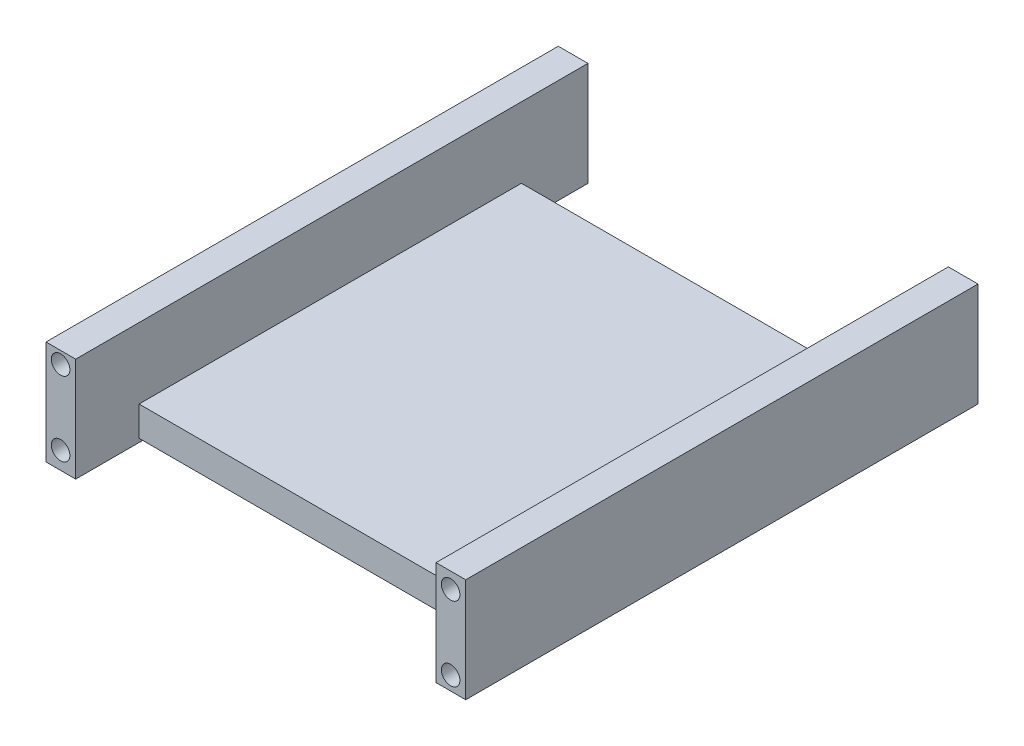
SolidWorks part; units mm, degrees
ref_plane "前视基准面" through (0, 0, 0) normal (0, 0, 1) x (1, 0, 0)
ref_plane "上视基准面" through (0, 0, 0) normal (0, 1, 0) x (1, 0, 0)
ref_plane "右视基准面" through (0, 0, 0) normal (1, 0, 0) x (0, 0, -1)
sketch "草图1" plane through (0, 0, 0) normal (1, 0, 0) x (0, 0, -1)
  line L1 (-69, 14) -> (69, 14)
  line L2 (-69, 14) -> (-69, -14)
  line L3 (-69, -14) -> (69, -14)
  line L4 (69, 14) -> (69, -14)
  line L5 (-69, 14) -> (69, -14) construction
  line L6 (-69, -14) -> (69, 14) construction
  point P0 (0, 0)
  dimension "D1" = 138
  dimension "D2" = 28
extrude "凸台-拉伸1" add sketch "草图1" along normal blind 8
sketch "草图2" plane through (0, 0, 0) normal (-1, 0, 0) x (0, 0, 1)
  line L0 (69, -14) -> (-69, -14) construction
  line L1 (-51, -6) -> (52, -6)
  line L2 (-51, -6) -> (-51, -14)
  line L3 (-51, -14) -> (52, -14)
  line L4 (52, -6) -> (52, -14)
  line L5 (-69, -14) -> (-69, 14) construction
  dimension "D1" = 18
  dimension "D2" = 103
  dimension "D3" = 8
extrude "凸台-拉伸2" add sketch "草图2" along normal blind 97
sketch "草图3" plane through (-97, 0, 0) normal (-1, 0, 0) x (0, 0, 1)
  line L1 (69.0702, -14.9897) -> (-68.9298, -14.9897)
  line L2 (69.0702, -14.9897) -> (69.0702, 13.0103)
  line L3 (69.0702, 13.0103) -> (-68.9298, 13.0103)
  line L4 (-68.9298, -14.9897) -> (-68.9298, 13.0103)
  dimension "D1" = 28
  dimension "D2" = 138
extrude "凸台-拉伸3" add sketch "草图3" along normal blind 8
sketch "草图4" plane through (0, 0, 69.0702) normal (0, 0, 1) x (1, 0, 0)
  circle A0 centre (-101.0733, 9.7314) radius 2.5
  circle A1 centre (3.9267, 9.7314) radius 2.5
  circle A2 centre (3.9267, -10.2686) radius 2.5
  circle A3 centre (-101.0733, -10.2686) radius 2.5
  dimension "D1" = 2
  dimension "D3" = 105
  dimension "D2" = 2
extrude "切除-拉伸1" cut sketch "草图4" against normal blind 5
sketch "草图5" plane through (0, 0, -69) normal (0, 0, -1) x (-1, 0, 0)
  line L0 (-8, 14) -> (0, 14) construction
  line L1 (-8, -14) -> (-8, 14) construction
  circle A0 centre (-4, 10) radius 2.5
  circle A1 centre (101, 10) radius 2.5
  circle A2 centre (101, -10) radius 2.5
  circle A3 centre (-4, -10) radius 2.5
  point P2 (-4, 14)
  dimension "D1" = 2
  dimension "D5" = 105
  dimension "D3" = 4
  dimension "D4" = 4
  dimension "D2" = 2
extrude "切除-拉伸2" cut sketch "草图5" against normal blind 5
